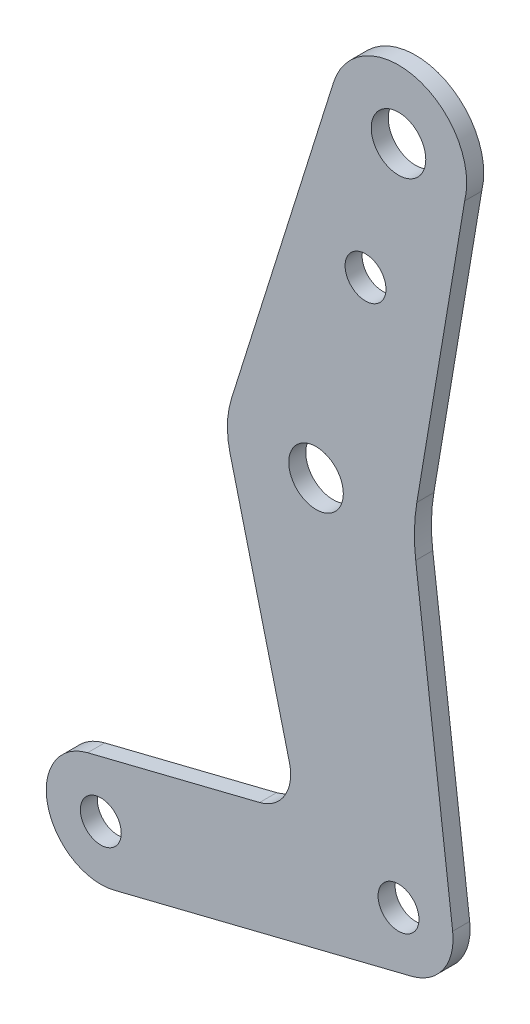
SolidWorks part; units mm, degrees
ref_plane "Front Plane" through (0, 0, 0) normal (0, 0, 1) x (1, 0, 0)
ref_plane "Top Plane" through (0, 0, 0) normal (0, 1, 0) x (1, 0, 0)
ref_plane "Right Plane" through (0, 0, 0) normal (1, 0, 0) x (0, 0, -1)
sketch "Sketch1" plane through (0, 0, 0) normal (0, 0, 1) x (1, 0, 0)
  line L0 (0, 0) -> (43.6633, 10.8865) construction
  line L1 (43.6633, 10.8865) -> (25.5377, 83.5841) construction
  line L2 (31.5672, 59.4013) -> (43.6633, 107.9161) construction
  line L3 (43.6633, 10.8865) -> (43.6633, 107.9161) construction
  line L4 (-3.1917, 12.8014) -> (3.1917, -12.8014) construction
  line L5 (-1.9354, 7.7624) -> (23.2923, 14.0523)
  line L6 (27.6626, 21.3256) -> (18.9534, 56.2563)
  line L7 (19.1648, 63.2974) -> (34.123, 110.9131)
  line L9 (0, 0) -> (9.4372, 0) construction
  line L10 (1.9354, -7.7624) -> (45.5987, 3.1241)
  line L11 (43.6633, 10.8865) -> (45.5987, 3.1241) construction
  line L12 (43.6633, 10.8865) -> (55.8101, 13.915) construction
  line L13 (51.6044, 11.8555) -> (46.187, 56.2521)
  line L14 (46.354, 63.7035) -> (53.3663, 105.4968)
  line L15 (22.4221, 113.2121) -> (64.9045, 102.62) construction
  circle A0 centre (0, 0) radius 3
  arc A1 (-1.9354, 7.7624) -> (1.9354, -7.7624) centre (0, 0) ccw
  arc A2 (23.2923, 14.0523) -> (27.6626, 21.3256) centre (21.8408, 19.8741) ccw
  arc A3 (45.5987, 3.1241) -> (51.6044, 11.8555) centre (43.6633, 10.8865) ccw
  circle A4 centre (43.6633, 107.9161) radius 4
  arc A6 (46.187, 56.2521) -> (46.354, 63.7035) centre (71.9956, 59.4013) cw
  arc A7 (53.3663, 105.4968) -> (34.123, 110.9131) centre (43.6633, 107.9161) ccw
  arc A8 (18.9534, 56.2563) -> (19.1648, 63.2974) centre (31.5672, 59.4013) cw
  circle A9 centre (31.5672, 59.4013) radius 4
  circle A10 centre (38.8249, 88.5101) radius 3
  circle A11 centre (43.6633, 10.8865) radius 3
  point P10 (0, 0)
  point P19 (29.1141, 15.5039)
  point P28 (43.6633, 107.9161)
  point P31 (0, 0)
  point P32 (31.6218, 59.6201)
  point P49 (18.0682, 59.8066)
  dimension "D5" = 6
  dimension "D6" = 16
  dimension "D9" = 6
  dimension "D10" = 50
  dimension "D11" = 10
  dimension "D12" = 8
  dimension "D13" = 26
  dimension "D15" = 13
  dimension "D16" = 8
  dimension "D17" = 6
  dimension "D19" = 6
  dimension "D1" = 45
  dimension "D2" = 50
  dimension "D3" = 14
  dimension "D4" = 14
  dimension "D8" = 14
  dimension "D14" = 40.4284
  dimension "D18" = 20
extrude "Boss-Extrude1" add sketch "Sketch1" along normal blind 2.5
